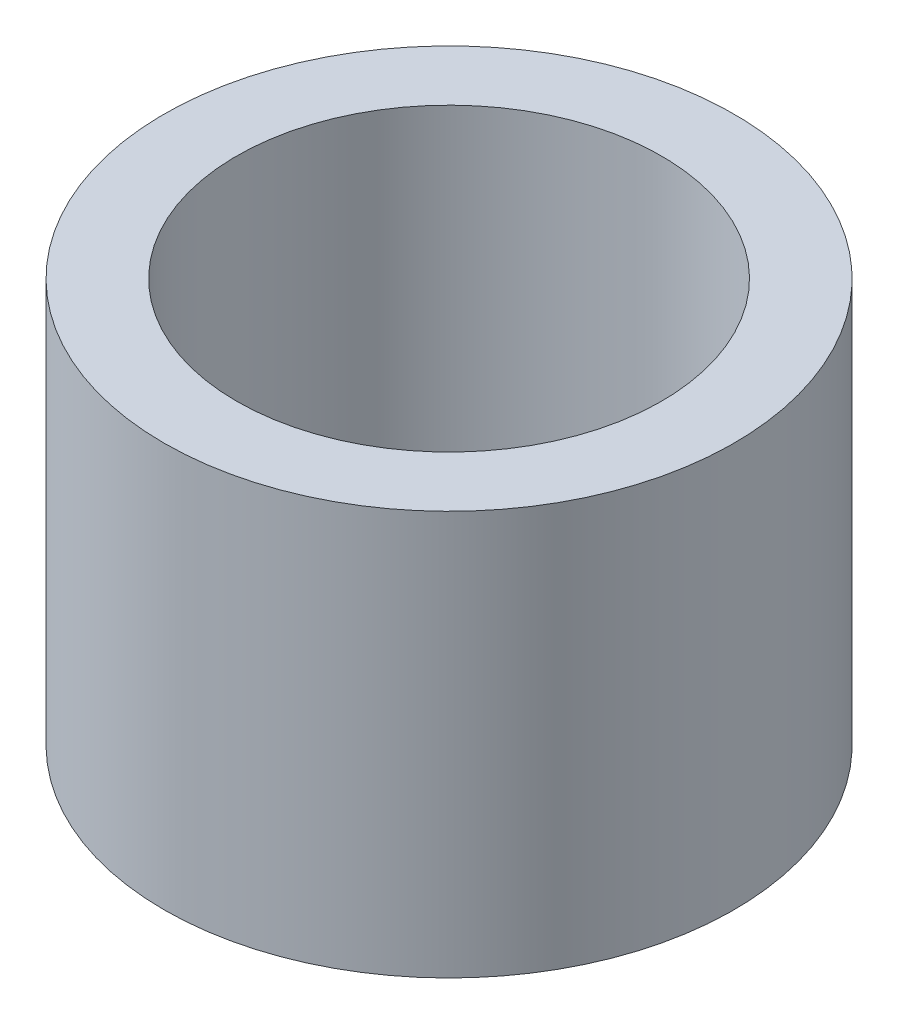
SolidWorks part; units mm, degrees
material "Natural Rubber"
ref_plane "Front Plane" through (0, 0, 0) normal (0, 0, 1) x (1, 0, 0)
ref_plane "Top Plane" through (0, 0, 0) normal (0, 1, 0) x (1, 0, 0)
ref_plane "Right Plane" through (0, 0, 0) normal (1, 0, 0) x (0, 0, -1)
sketch "ProfileS" plane through (0, 0, 0) normal (0, 1, 0) x (1, 0, 0)
  circle A0 centre (0, 0) radius 5.5
  circle A1 centre (0, 0) radius 4.1
  dimension "OD" = 11
  dimension "RefID" = 8.2
  dimension "IDControl" = 1.4
extrude "Profile" add sketch "ProfileS" along normal mid plane 7.8
